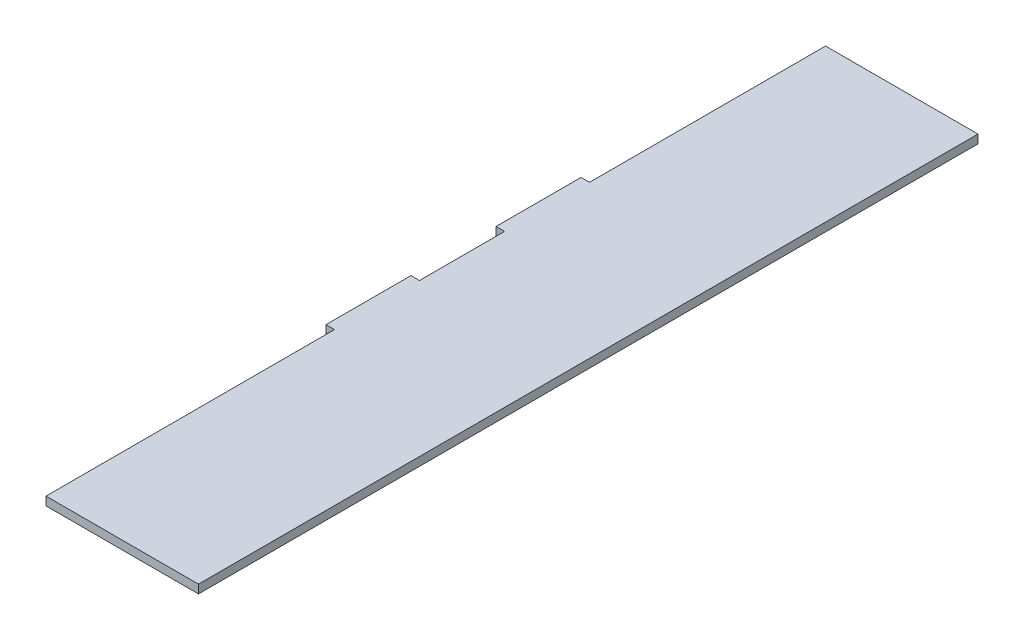
SolidWorks part; units mm, degrees
ref_plane "Front Plane" through (0, 0, 0) normal (0, 0, 1) x (1, 0, 0)
ref_plane "Top Plane" through (0, 0, 0) normal (0, 1, 0) x (1, 0, 0)
ref_plane "Right Plane" through (0, 0, 0) normal (1, 0, 0) x (0, 0, -1)
sketch "Sketch1" plane through (0, 0, 0) normal (0, 1, 0) x (1, 0, 0)
  line L1 (0, 0) -> (56.8, 0)
  line L2 (0, 0) -> (0, 275.1)
  line L3 (0, 275.1) -> (56.8, 275.1)
  line L4 (56.8, 0) -> (56.8, 275.1)
  dimension "D1" = 56.8
  dimension "D2" = 275.1
extrude "Boss-Extrude1" add sketch "Sketch1" along normal blind 3
sketch "Sketch2" plane through (0, 3, 0) normal (0, 1, 0) x (1, 0, 0)
  line L0 (0, 275.1) -> (0, 0) construction
  line L1 (0, 275.1) -> (3, 275.1)
  line L2 (0, 275.1) -> (0, 191.8)
  line L3 (0, 191.8) -> (3, 191.8)
  line L4 (3, 275.1) -> (3, 191.8)
  line L5 (0, 0) -> (3, 0)
  line L6 (0, 0) -> (0, 101.8)
  line L7 (0, 101.8) -> (3, 101.8)
  line L8 (3, 0) -> (3, 101.8)
  line L9 (0, 161.8) -> (3, 161.8)
  line L10 (0, 161.8) -> (0, 131.8)
  line L11 (0, 131.8) -> (3, 131.8)
  line L12 (3, 161.8) -> (3, 131.8)
  line L13 (0, 191.8) -> (0, 161.8) construction
  line L14 (0, 101.8) -> (0, 131.8) construction
  dimension "D1" = 3
  dimension "D2" = 30
  dimension "D3" = 30
  dimension "D4" = 83.3
extrude "Cut-Extrude1" cut sketch "Sketch2" against normal blind 5
